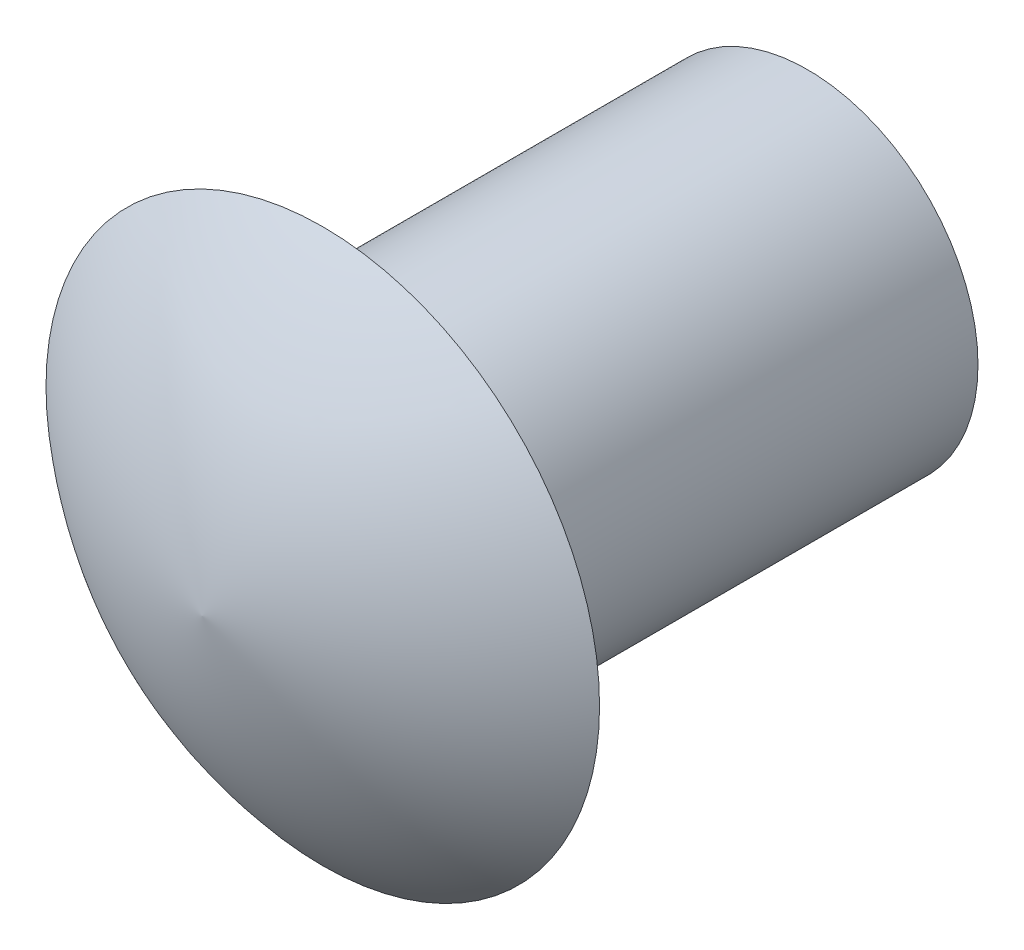
SolidWorks part; units mm, degrees
ref_plane "Front Plane" through (0, 0, 0) normal (0, 0, 1) x (1, 0, 0)
ref_plane "Top Plane" through (0, 0, 0) normal (0, 1, 0) x (1, 0, 0)
ref_plane "Right Plane" through (0, 0, 0) normal (1, 0, 0) x (0, 0, -1)
sketch "Sketch1" plane through (0, 0, 0) normal (0, 0, 1) x (1, 0, 0)
  circle A0 centre (0, 0) radius 11.1646
  dimension "D1" = 22.3291
extrude "Extrude1" add sketch "Sketch1" against normal blind 31.75
sketch "Sketch2" plane through (0, 0, 0) normal (1, 0, 0) x (0, 0, -1)
  line L0 (0, 0) -> (0, 18.1281)
  line L1 (0, 0) -> (-7.9004, 0)
  arc A0 (0, 18.1281) -> (-7.9004, 0) centre (25.3362, -3.6992) ccw
revolve "Revolve1" add sketch "Sketch2" angle 360 about L1
